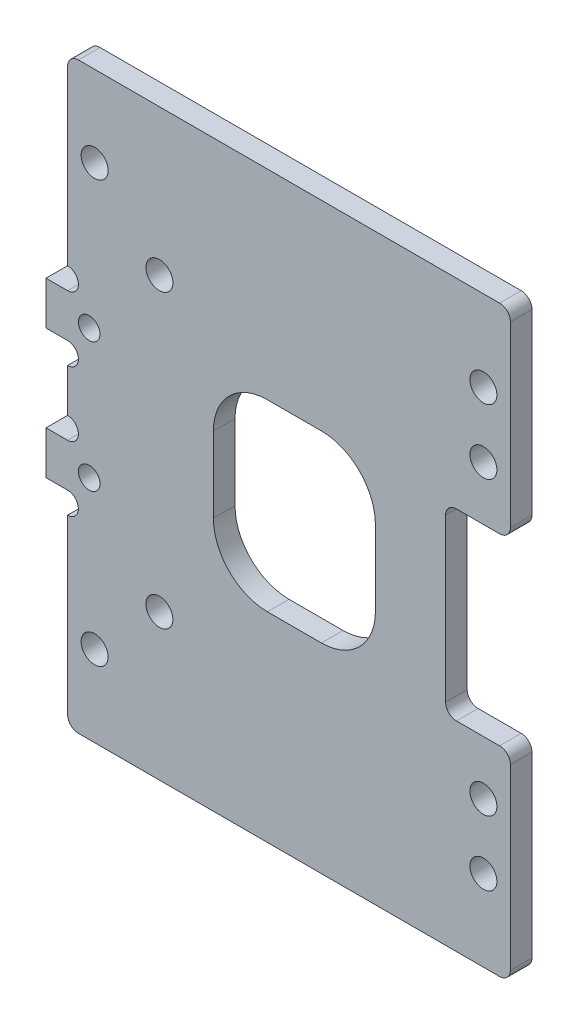
SolidWorks part; units mm, degrees
material "自訂玻璃纖維"
ref_plane "前基準面" through (0, 0, 0) normal (0, 0, 1) x (1, 0, 0)
ref_plane "上基準面" through (0, 0, 0) normal (0, 1, 0) x (1, 0, 0)
ref_plane "右基準面" through (0, 0, 0) normal (1, 0, 0) x (0, 0, -1)
sketch "草圖1" plane through (0, 0, 0) normal (0, 0, 1) x (1, 0, 0)
  line L0 (25.7147, 4.0447) -> (25.7147, -0.9553)
  line L1 (3.2147, 22.0447) -> (8.2147, 22.0447)
  line L2 (-1.7853, 17.0447) -> (-1.7853, 10.0447)
  line L3 (3.2147, 5.0447) -> (8.2147, 5.0447)
  line L4 (13.2147, 17.0447) -> (13.2147, 10.0447)
  line L5 (-14.2853, 40.5447) -> (24.7147, 40.5447)
  line L6 (-15.2853, 39.5447) -> (-15.2853, 23.5447)
  line L7 (25.7147, 39.5447) -> (25.7147, 28.5447)
  line L8 (25.7147, 28.5447) -> (25.7147, 23.0447)
  line L9 (24.7147, 22.0447) -> (20.7147, 22.0447)
  line L10 (25.7147, -0.9553) -> (25.7147, -12.4553)
  line L11 (24.7147, 5.0447) -> (20.7147, 5.0447)
  line L12 (19.7147, 21.0447) -> (19.7147, 6.0447)
  line L13 (24.7147, -13.4553) -> (-14.2853, -13.4553)
  line L14 (-15.2853, 15.5447) -> (-15.2853, 11.5447)
  line L15 (-15.2853, 21.5447) -> (-17.2853, 21.5447)
  line L16 (-17.2853, 9.5447) -> (-17.2853, 5.5447)
  line L17 (-15.2853, 17.5447) -> (-17.2853, 17.5447)
  line L18 (-17.2853, 21.5447) -> (-17.2853, 17.5447)
  line L19 (-15.2853, 5.5447) -> (-17.2853, 5.5447)
  line L20 (-15.2853, 9.5447) -> (-17.2853, 9.5447)
  line L21 (-15.2853, 3.5447) -> (-15.2853, -12.4553)
  circle A0 centre (-6.7853, 27.0447) radius 1.25
  circle A1 centre (23.2147, 27.0447) radius 1.25
  circle A2 centre (-6.7853, 0.0447) radius 1.25
  circle A3 centre (23.2147, 0.0447) radius 1.25
  arc A4 (-15.2853, 21.5447) -> (-15.2853, 23.5447) centre (-15.2853, 22.5447) ccw
  arc A5 (-1.7853, 10.0447) -> (3.2147, 5.0447) centre (3.2147, 10.0447) ccw
  arc A6 (8.2147, 5.0447) -> (13.2147, 10.0447) centre (8.2147, 10.0447) ccw
  arc A7 (8.2147, 22.0447) -> (13.2147, 17.0447) centre (8.2147, 17.0447) cw
  arc A8 (3.2147, 22.0447) -> (-1.7853, 17.0447) centre (3.2147, 17.0447) ccw
  arc A9 (25.7147, 4.0447) -> (24.7147, 5.0447) centre (24.7147, 4.0447) ccw
  arc A10 (20.7147, 5.0447) -> (19.7147, 6.0447) centre (20.7147, 6.0447) cw
  arc A11 (20.7147, 22.0447) -> (19.7147, 21.0447) centre (20.7147, 21.0447) ccw
  arc A12 (24.7147, 22.0447) -> (25.7147, 23.0447) centre (24.7147, 23.0447) ccw
  arc A13 (24.7147, 40.5447) -> (25.7147, 39.5447) centre (24.7147, 39.5447) cw
  arc A14 (-15.2853, 39.5447) -> (-14.2853, 40.5447) centre (-14.2853, 39.5447) cw
  arc A15 (25.7147, -12.4553) -> (24.7147, -13.4553) centre (24.7147, -12.4553) cw
  arc A16 (-15.2853, -12.4553) -> (-14.2853, -13.4553) centre (-14.2853, -12.4553) ccw
  circle A17 centre (-12.7853, 33.0447) radius 1.25
  circle A18 centre (23.2147, 33.0447) radius 1.25
  circle A19 centre (23.2147, -5.9553) radius 1.25
  circle A20 centre (-12.7853, -5.9553) radius 1.25
  circle A21 centre (-13.2853, 19.5447) radius 1
  circle A22 centre (-13.2853, 7.5447) radius 1
  arc A23 (-15.2853, 17.5447) -> (-15.2853, 15.5447) centre (-15.2853, 16.5447) cw
  arc A24 (-15.2853, 9.5447) -> (-15.2853, 11.5447) centre (-15.2853, 10.5447) ccw
  arc A25 (-15.2853, 5.5447) -> (-15.2853, 3.5447) centre (-15.2853, 4.5447) cw
  point P32 (25.7147, 5.0447)
  point P35 (19.7147, 5.0447)
  point P48 (-15.2853, 40.5447)
  point P53 (-15.2853, -13.4553)
  point P79 (-16.2853, 9.5447)
  dimension "D1" = 2.5
  dimension "D2" = 30
  dimension "D3" = 30
  dimension "D4" = 27
  dimension "D5" = 27
  dimension "D6" = 2
  dimension "D7" = 4
  dimension "D8" = 2
  dimension "D13" = 0
  dimension "D14" = 5
  dimension "D20" = 1
  dimension "D21" = 1
  dimension "D22" = 2.5
  dimension "D23" = 7.5
  dimension "D24" = 2.5
  dimension "D25" = 2.5
  dimension "D26" = 7.5
  dimension "D27" = 2.5
  dimension "D28" = 7.5
  dimension "D29" = 7.5
  dimension "D30" = 12
  dimension "D9" = 5
  dimension "D10" = 10
  dimension "D11" = 5
  dimension "D12" = 5
  dimension "D15" = 54
  dimension "D16" = 10
  dimension "D18" = 2.5
  dimension "D19" = 6
extrude "填料-伸長1" add sketch "草圖1" along normal blind 2
